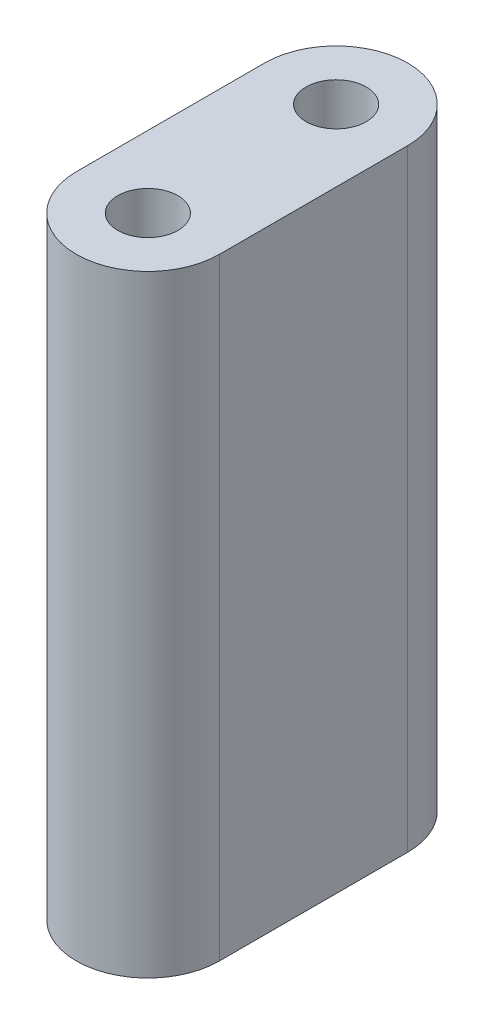
SolidWorks part; units mm, degrees
ref_plane "Front Plane" through (0, 0, 0) normal (0, 0, 1) x (1, 0, 0)
ref_plane "Top Plane" through (0, 0, 0) normal (0, 1, 0) x (1, 0, 0)
ref_plane "Right Plane" through (0, 0, 0) normal (1, 0, 0) x (0, 0, -1)
sketch "Sketch1" plane through (0, 0, 0) normal (0, 1, 0) x (1, 0, 0)
  line L0 (0, -5) -> (0, 5) construction
  line L1 (-3.8, -5) -> (-3.8, 5)
  line L2 (3.8, -5) -> (3.8, 5)
  arc A1 (-3.8, -5) -> (3.8, -5) centre (0, -5) ccw
  arc A2 (3.8, 5) -> (-3.8, 5) centre (0, 5) ccw
  point P2 (0, 0)
  dimension "D1" = 10
  dimension "D2" = 3.8
extrude "Boss-Extrude1" add sketch "Sketch1" along normal blind 32.5
sketch "Sketch2" plane through (0, 32.5, 0) normal (0, 1, 0) x (1, 0, 0)
  circle A0 centre (0, 5) radius 1.6
  circle A1 centre (0, -5) radius 1.6
  dimension "D1" = 3.2
extrude "Cut-Extrude1" cut sketch "Sketch2" against normal through all
